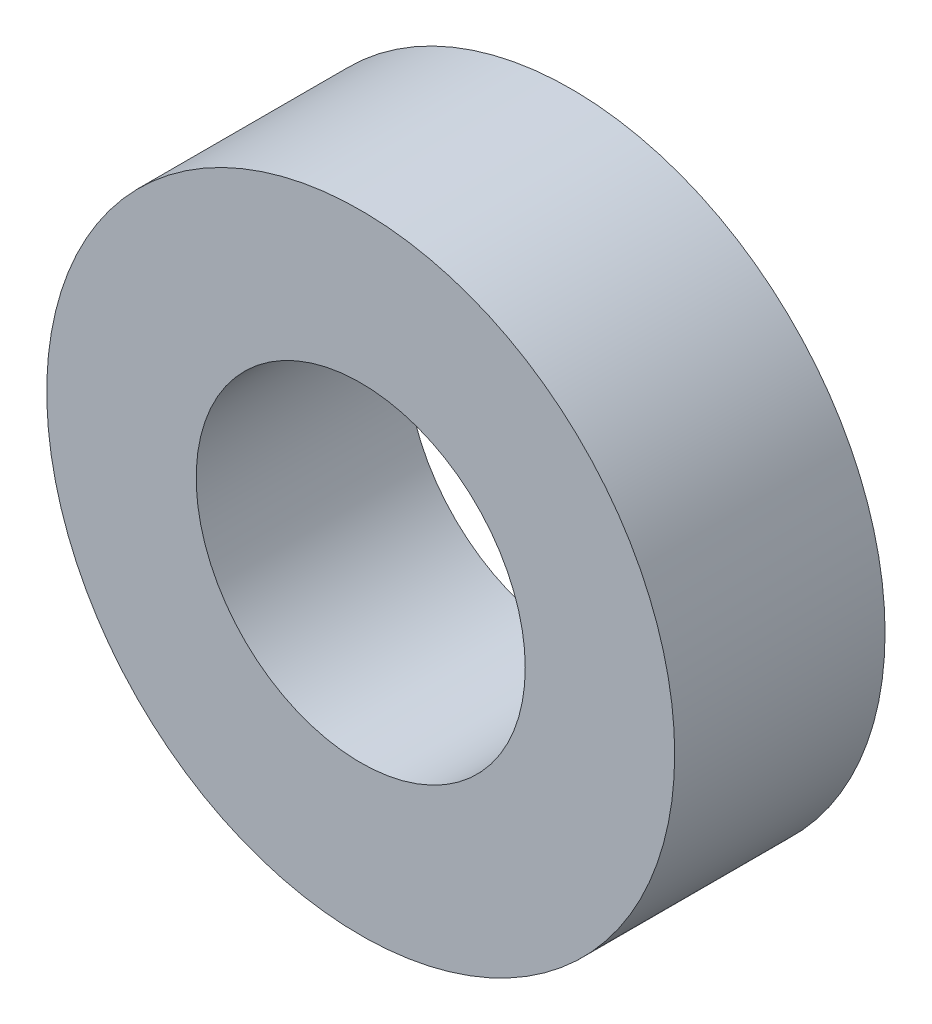
SolidWorks part; units mm, degrees
material "Nylon 101"
ref_plane "Front Plane" through (0, 0, 0) normal (0, 0, 1) x (1, 0, 0)
ref_plane "Top Plane" through (0, 0, 0) normal (0, 1, 0) x (1, 0, 0)
ref_plane "Right Plane" through (0, 0, 0) normal (1, 0, 0) x (0, 0, -1)
sketch "Sketch1" plane through (0, 0, 0) normal (0, 0, 1) x (1, 0, 0)
  circle A0 centre (0, 0) radius 4.7498
  circle A1 centre (0, 0) radius 2.4892
  dimension "D1" = 9.4996
  dimension "D2" = 4.9784
extrude "Boss-Extrude1" add sketch "Sketch1" along normal blind 3.1826
